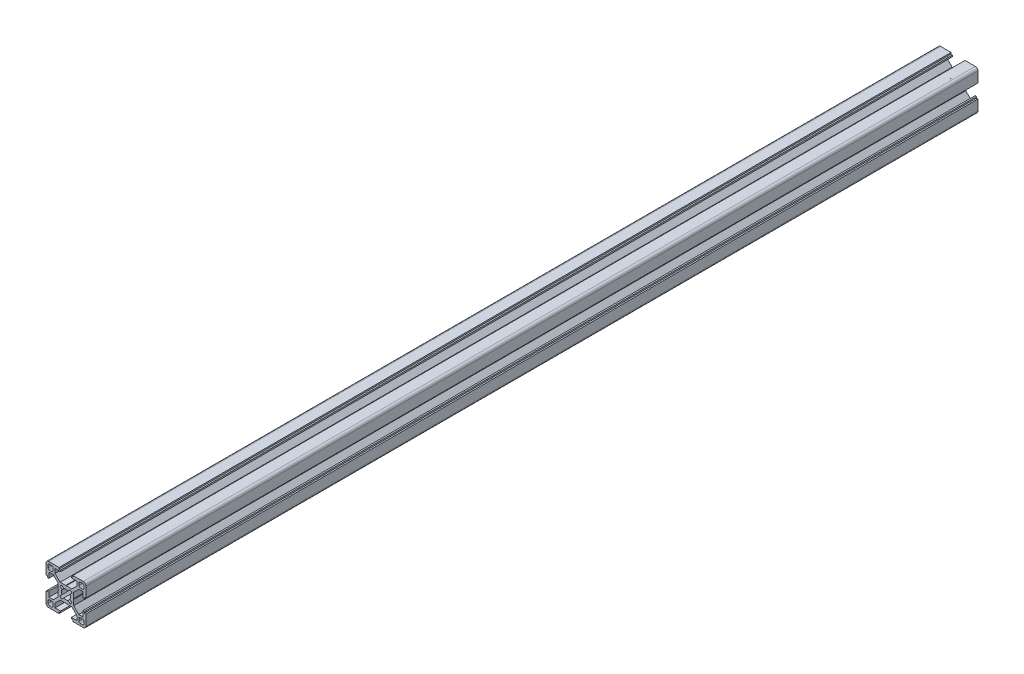
SolidWorks part; units mm, degrees
material "3003 Alloy"
ref_plane "Frente" through (0, 0, 0) normal (0, 0, 1) x (1, 0, 0)
ref_plane "Topo" through (0, 0, 0) normal (0, 1, 0) x (1, 0, 0)
ref_plane "Lateral" through (0, 0, 0) normal (1, 0, 0) x (0, 0, -1)
sketch "Sketch1" plane through (0, 0, 0) normal (0, 0, 1) x (1, 0, 0)
  line L0 (-13.5, 10.7) -> (-13.5, 12.5)
  line L1 (-12.5, 13.5) -> (-10.7, 13.5)
  line L2 (-9.7, 12.5) -> (-9.7, 10.7)
  line L3 (-10.7, 9.7) -> (-12.5, 9.7)
  line L4 (-13.5, -12.5) -> (-13.5, -10.7)
  line L5 (-12.5, -9.7) -> (-10.7, -9.7)
  line L6 (-9.7, -10.7) -> (-9.7, -12.5)
  line L7 (-10.7, -13.5) -> (-12.5, -13.5)
  line L8 (13.5, -10.7) -> (13.5, -12.5)
  line L9 (12.5, -13.5) -> (10.7, -13.5)
  line L10 (9.7, -12.5) -> (9.7, -10.7)
  line L11 (10.7, -9.7) -> (12.5, -9.7)
  line L12 (13.5, 12.5) -> (13.5, 10.7)
  line L13 (12.5, 9.7) -> (10.7, 9.7)
  line L14 (9.7, 10.7) -> (9.7, 12.5)
  line L15 (10.7, 13.5) -> (12.5, 13.5)
  line L16 (-1.5907, -3.0049) -> (-3.1817, -4.5959)
  line L17 (-3.1817, -4.5959) -> (-4.5959, -3.1817)
  line L18 (-4.5959, -3.1817) -> (-3.0049, -1.5907)
  line L19 (-3.0049, 1.5907) -> (-4.5959, 3.1817)
  line L20 (-4.5959, 3.1817) -> (-3.1817, 4.5959)
  line L21 (-3.1817, 4.5959) -> (-1.5907, 3.0049)
  line L22 (1.5907, 3.0049) -> (3.1817, 4.5959)
  line L23 (3.1817, 4.5959) -> (4.5959, 3.1817)
  line L24 (4.5959, 3.1817) -> (3.0049, 1.5907)
  line L25 (3.0049, -1.5907) -> (4.5959, -3.1817)
  line L26 (4.5959, -3.1817) -> (3.1817, -4.5959)
  line L27 (3.1817, -4.5959) -> (1.5907, -3.0049)
  line L28 (0, -5.55) -> (0.25, -5.8)
  line L29 (0.25, -5.8) -> (4.3858, -5.8)
  line L30 (4.3858, -5.8) -> (8.2, -9.6142)
  line L31 (8.2, -9.6142) -> (8.2, -12.8)
  line L32 (8.2, -12.8) -> (4.1, -12.8)
  line L33 (4.1, -12.8) -> (4.1, -13.9)
  line L34 (4.1, -13.9) -> (5.2, -13.9)
  line L35 (5.2, -13.9) -> (5.2, -15)
  line L36 (5.2, -15) -> (13, -15)
  line L37 (15, -13) -> (15, -5.2)
  line L38 (15, -5.2) -> (13.9, -5.2)
  line L39 (13.9, -5.2) -> (13.9, -4.1)
  line L40 (13.9, -4.1) -> (12.8, -4.1)
  line L41 (12.8, -4.1) -> (12.8, -8.2)
  line L42 (12.8, -8.2) -> (9.6142, -8.2)
  line L43 (9.6142, -8.2) -> (5.8, -4.3858)
  line L44 (5.8, -4.3858) -> (5.8, -0.25)
  line L45 (5.8, -0.25) -> (5.55, 0)
  line L46 (5.55, 0) -> (5.8, 0.25)
  line L47 (5.8, 0.25) -> (5.8, 4.3858)
  line L48 (5.8, 4.3858) -> (9.6142, 8.2)
  line L49 (9.6142, 8.2) -> (12.8, 8.2)
  line L50 (12.8, 8.2) -> (12.8, 4.1)
  line L51 (12.8, 4.1) -> (13.9, 4.1)
  line L52 (13.9, 4.1) -> (13.9, 5.2)
  line L53 (13.9, 5.2) -> (15, 5.2)
  line L54 (15, 5.2) -> (15, 13)
  line L55 (13, 15) -> (5.2, 15)
  line L56 (5.2, 15) -> (5.2, 13.9)
  line L57 (5.2, 13.9) -> (4.1, 13.9)
  line L58 (4.1, 13.9) -> (4.1, 12.8)
  line L59 (4.1, 12.8) -> (8.2, 12.8)
  line L60 (8.2, 12.8) -> (8.2, 9.6142)
  line L61 (8.2, 9.6142) -> (4.3858, 5.8)
  line L62 (4.3858, 5.8) -> (0.25, 5.8)
  line L63 (0.25, 5.8) -> (0, 5.55)
  line L64 (0, 5.55) -> (-0.25, 5.8)
  line L65 (-0.25, 5.8) -> (-4.3858, 5.8)
  line L66 (-4.3858, 5.8) -> (-8.2, 9.6142)
  line L67 (-8.2, 9.6142) -> (-8.2, 12.8)
  line L68 (-8.2, 12.8) -> (-4.1, 12.8)
  line L69 (-4.1, 12.8) -> (-4.1, 13.9)
  line L70 (-4.1, 13.9) -> (-5.2, 13.9)
  line L71 (-5.2, 13.9) -> (-5.2, 15)
  line L72 (-5.2, 15) -> (-13, 15)
  line L73 (-15, 13) -> (-15, 5.2)
  line L74 (-15, 5.2) -> (-13.9, 5.2)
  line L75 (-13.9, 5.2) -> (-13.9, 4.1)
  line L76 (-13.9, 4.1) -> (-12.8, 4.1)
  line L77 (-12.8, 4.1) -> (-12.8, 8.2)
  line L78 (-12.8, 8.2) -> (-9.6142, 8.2)
  line L79 (-9.6142, 8.2) -> (-5.8, 4.3858)
  line L80 (-5.8, 4.3858) -> (-5.8, 0.25)
  line L81 (-5.8, 0.25) -> (-5.55, 0)
  line L82 (-5.55, 0) -> (-5.8, -0.25)
  line L83 (-5.8, -0.25) -> (-5.8, -4.3858)
  line L84 (-5.8, -4.3858) -> (-9.6142, -8.2)
  line L85 (-9.6142, -8.2) -> (-12.8, -8.2)
  line L86 (-12.8, -8.2) -> (-12.8, -4.1)
  line L87 (-12.8, -4.1) -> (-13.9, -4.1)
  line L88 (-13.9, -4.1) -> (-13.9, -5.2)
  line L89 (-13.9, -5.2) -> (-15, -5.2)
  line L90 (-15, -5.2) -> (-15, -13)
  line L91 (-13, -15) -> (-5.2, -15)
  line L92 (-5.2, -15) -> (-5.2, -13.9)
  line L93 (-5.2, -13.9) -> (-4.1, -13.9)
  line L94 (-4.1, -13.9) -> (-4.1, -12.8)
  line L95 (-4.1, -12.8) -> (-8.2, -12.8)
  line L96 (-8.2, -12.8) -> (-8.2, -9.6142)
  line L97 (-8.2, -9.6142) -> (-4.3858, -5.8)
  line L98 (-4.3858, -5.8) -> (-0.25, -5.8)
  line L99 (-0.25, -5.8) -> (0, -5.55)
  arc A0 (-13.5, 12.5) -> (-12.5, 13.5) centre (-12.5, 12.5) cw
  arc A1 (-10.7, 13.5) -> (-9.7, 12.5) centre (-10.7, 12.5) cw
  arc A2 (-9.7, 10.7) -> (-10.7, 9.7) centre (-10.7, 10.7) cw
  arc A3 (-12.5, 9.7) -> (-13.5, 10.7) centre (-12.5, 10.7) cw
  arc A4 (-13.5, -10.7) -> (-12.5, -9.7) centre (-12.5, -10.7) cw
  arc A5 (-10.7, -9.7) -> (-9.7, -10.7) centre (-10.7, -10.7) cw
  arc A6 (-9.7, -12.5) -> (-10.7, -13.5) centre (-10.7, -12.5) cw
  arc A7 (-12.5, -13.5) -> (-13.5, -12.5) centre (-12.5, -12.5) cw
  arc A8 (13.5, -12.5) -> (12.5, -13.5) centre (12.5, -12.5) cw
  arc A9 (10.7, -13.5) -> (9.7, -12.5) centre (10.7, -12.5) cw
  arc A10 (9.7, -10.7) -> (10.7, -9.7) centre (10.7, -10.7) cw
  arc A11 (12.5, -9.7) -> (13.5, -10.7) centre (12.5, -10.7) cw
  arc A12 (13.5, 10.7) -> (12.5, 9.7) centre (12.5, 10.7) cw
  arc A13 (10.7, 9.7) -> (9.7, 10.7) centre (10.7, 10.7) cw
  arc A14 (9.7, 12.5) -> (10.7, 13.5) centre (10.7, 12.5) cw
  arc A15 (12.5, 13.5) -> (13.5, 12.5) centre (12.5, 12.5) cw
  arc A16 (1.5907, -3.0049) -> (-1.5907, -3.0049) centre (0, 0) cw
  arc A17 (-3.0049, -1.5907) -> (-3.0049, 1.5907) centre (0, 0) cw
  arc A18 (-1.5907, 3.0049) -> (1.5907, 3.0049) centre (0, 0) cw
  arc A19 (3.0049, 1.5907) -> (3.0049, -1.5907) centre (0, 0) cw
  arc A20 (13, -15) -> (15, -13) centre (13, -13) ccw
  arc A21 (15, 13) -> (13, 15) centre (13, 13) ccw
  arc A22 (-13, 15) -> (-15, 13) centre (-13, 13) ccw
  arc A23 (-15, -13) -> (-13, -15) centre (-13, -13) ccw
extrude "Boss-Extrude1" add sketch "Sketch1" against normal mid plane 670
